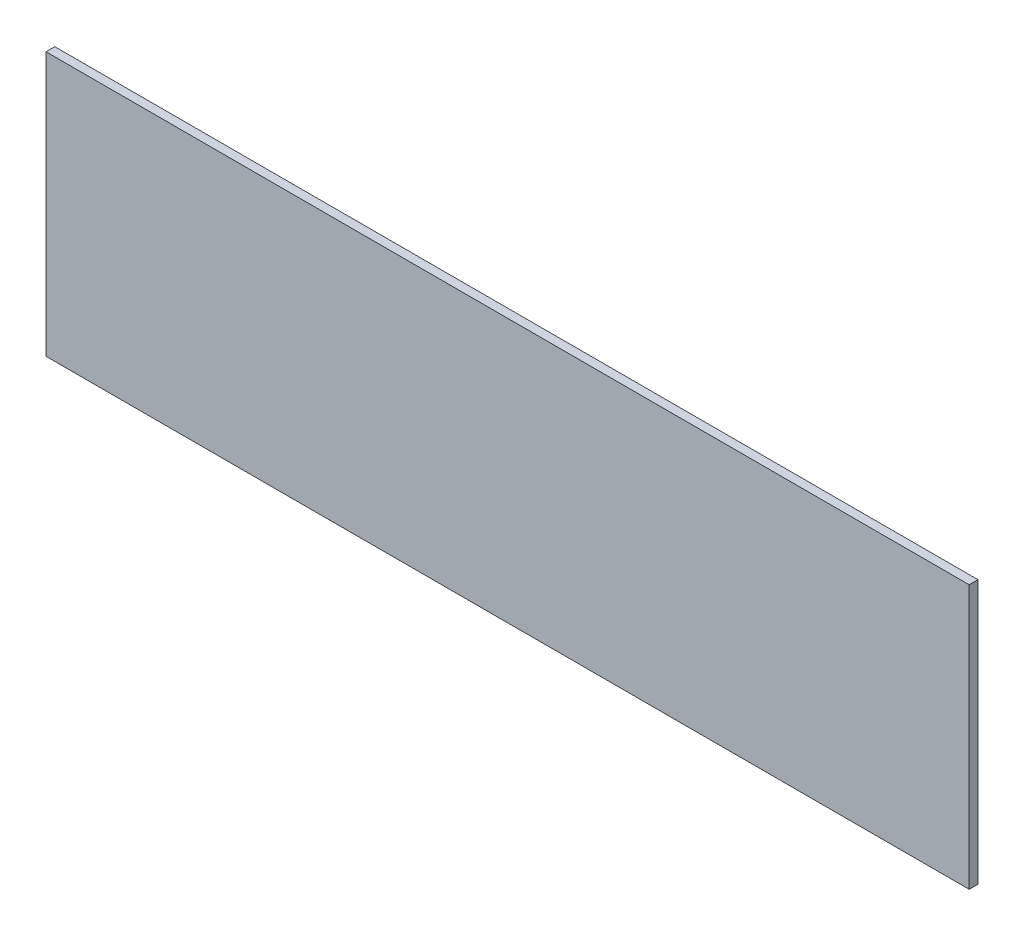
SolidWorks part; units mm, degrees
ref_plane "Front Plane" through (0, 0, 0) normal (0, 0, 1) x (1, 0, 0)
ref_plane "Top Plane" through (0, 0, 0) normal (0, 1, 0) x (1, 0, 0)
ref_plane "Right Plane" through (0, 0, 0) normal (1, 0, 0) x (0, 0, -1)
sketch "Sketch1" plane through (0, 0, 0) normal (0, 0, 1) x (1, 0, 0)
  line L0 (-52.5, 15) -> (-52.5, -15)
  line L1 (-52.5, -15) -> (52.5, -15)
  line L2 (52.5, -15) -> (52.5, 15)
  line L3 (52.5, 15) -> (-52.5, 15)
  point P3 (-52.5, 0)
  point P6 (0, 15)
  dimension "D1" = 105
  dimension "D2" = 30
extrude "Boss-Extrude1" add sketch "Sketch1" along normal blind 1
